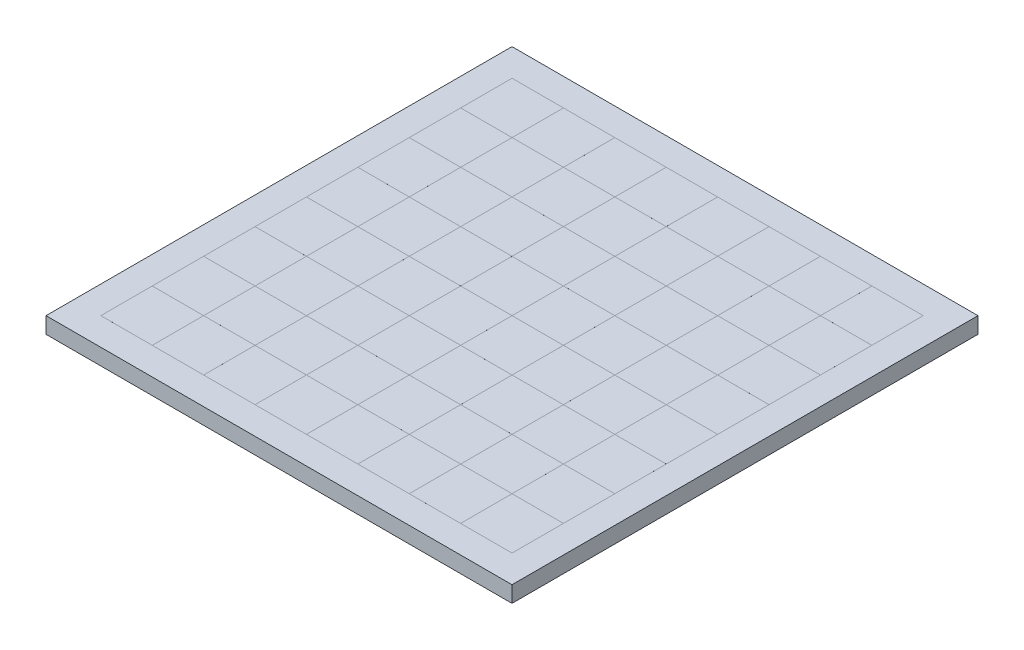
SolidWorks part; units mm, degrees
ref_plane "Front Plane" through (0, 0, 0) normal (0, 0, 1) x (1, 0, 0)
ref_plane "Top Plane" through (0, 0, 0) normal (0, 1, 0) x (1, 0, 0)
ref_plane "Right Plane" through (0, 0, 0) normal (1, 0, 0) x (0, 0, -1)
sketch "Sketch1" plane through (0, 0, 0) normal (0, 1, 0) x (1, 0, 0)
  line L1 (0, 0) -> (431.8, 0)
  line L2 (0, 0) -> (0, 431.8)
  line L3 (0, 431.8) -> (431.8, 431.8)
  line L4 (431.8, 0) -> (431.8, 431.8)
  dimension "D1" = 431.8
  dimension "D2" = 431.8
extrude "Boss-Extrude1" add sketch "Sketch1" along normal blind 5
sketch "Sketch2" plane through (0, 5, 0) normal (0, 1, 0) x (1, 0, 0)
  line L0 (0, 0) -> (431.8, 0) construction
  line L5 (25.4, 73.025) -> (73.025, 73.025)
  line L6 (25.4, 73.025) -> (25.4, 25.4)
  line L7 (25.4, 25.4) -> (73.025, 25.4)
  line L8 (73.025, 73.025) -> (73.025, 25.4)
  line L9 (0, 431.8) -> (0, 0) construction
  line L10 (25.4, 120.655) -> (25.4, 73.03)
  line L11 (25.4, 120.655) -> (73.025, 120.655)
  line L12 (73.025, 120.655) -> (73.025, 73.03)
  line L13 (25.4, 73.03) -> (73.025, 73.03)
  line L14 (25.4, 168.285) -> (25.4, 120.66)
  line L15 (25.4, 168.285) -> (73.025, 168.285)
  line L16 (73.025, 168.285) -> (73.025, 120.66)
  line L17 (25.4, 120.66) -> (73.025, 120.66)
  line L18 (25.4, 215.915) -> (25.4, 168.29)
  line L19 (25.4, 215.915) -> (73.025, 215.915)
  line L20 (73.025, 215.915) -> (73.025, 168.29)
  line L21 (25.4, 168.29) -> (73.025, 168.29)
  line L22 (25.4, 263.545) -> (25.4, 215.92)
  line L23 (25.4, 263.545) -> (73.025, 263.545)
  line L24 (73.025, 263.545) -> (73.025, 215.92)
  line L25 (25.4, 215.92) -> (73.025, 215.92)
  line L26 (25.4, 311.175) -> (25.4, 263.55)
  line L27 (25.4, 311.175) -> (73.025, 311.175)
  line L28 (73.025, 311.175) -> (73.025, 263.55)
  line L29 (25.4, 263.55) -> (73.025, 263.55)
  line L30 (25.4, 358.805) -> (25.4, 311.18)
  line L31 (25.4, 358.805) -> (73.025, 358.805)
  line L32 (73.025, 358.805) -> (73.025, 311.18)
  line L33 (25.4, 311.18) -> (73.025, 311.18)
  line L34 (25.4, 406.435) -> (25.4, 358.81)
  line L35 (25.4, 406.435) -> (73.025, 406.435)
  line L36 (73.025, 406.435) -> (73.025, 358.81)
  line L37 (25.4, 358.81) -> (73.025, 358.81)
  line L38 (73.03, 120.655) -> (73.03, 73.03)
  line L39 (73.03, 120.655) -> (120.655, 120.655)
  line L40 (120.655, 120.655) -> (120.655, 73.03)
  line L41 (73.03, 73.03) -> (120.655, 73.03)
  line L42 (73.03, 168.285) -> (73.03, 120.66)
  line L43 (73.03, 168.285) -> (120.655, 168.285)
  line L44 (120.655, 168.285) -> (120.655, 120.66)
  line L45 (73.03, 120.66) -> (120.655, 120.66)
  line L46 (73.03, 215.915) -> (73.03, 168.29)
  line L47 (73.03, 215.915) -> (120.655, 215.915)
  line L48 (120.655, 215.915) -> (120.655, 168.29)
  line L49 (73.03, 168.29) -> (120.655, 168.29)
  line L50 (73.03, 263.545) -> (73.03, 215.92)
  line L51 (73.03, 263.545) -> (120.655, 263.545)
  line L52 (120.655, 263.545) -> (120.655, 215.92)
  line L53 (73.03, 215.92) -> (120.655, 215.92)
  line L54 (73.03, 311.175) -> (73.03, 263.55)
  line L55 (73.03, 311.175) -> (120.655, 311.175)
  line L56 (120.655, 311.175) -> (120.655, 263.55)
  line L57 (73.03, 263.55) -> (120.655, 263.55)
  line L58 (73.03, 358.805) -> (73.03, 311.18)
  line L59 (73.03, 358.805) -> (120.655, 358.805)
  line L60 (120.655, 358.805) -> (120.655, 311.18)
  line L61 (73.03, 311.18) -> (120.655, 311.18)
  line L62 (73.03, 406.435) -> (73.03, 358.81)
  line L63 (73.03, 406.435) -> (120.655, 406.435)
  line L64 (120.655, 406.435) -> (120.655, 358.81)
  line L65 (73.03, 358.81) -> (120.655, 358.81)
  line L66 (120.66, 120.655) -> (120.66, 73.03)
  line L67 (120.66, 120.655) -> (168.285, 120.655)
  line L68 (168.285, 120.655) -> (168.285, 73.03)
  line L69 (120.66, 73.03) -> (168.285, 73.03)
  line L70 (120.66, 168.285) -> (120.66, 120.66)
  line L71 (120.66, 168.285) -> (168.285, 168.285)
  line L72 (168.285, 168.285) -> (168.285, 120.66)
  line L73 (120.66, 120.66) -> (168.285, 120.66)
  line L74 (120.66, 215.915) -> (120.66, 168.29)
  line L75 (120.66, 215.915) -> (168.285, 215.915)
  line L76 (168.285, 215.915) -> (168.285, 168.29)
  line L77 (120.66, 168.29) -> (168.285, 168.29)
  line L78 (120.66, 263.545) -> (120.66, 215.92)
  line L79 (120.66, 263.545) -> (168.285, 263.545)
  line L80 (168.285, 263.545) -> (168.285, 215.92)
  line L81 (120.66, 215.92) -> (168.285, 215.92)
  line L82 (120.66, 311.175) -> (120.66, 263.55)
  line L83 (120.66, 311.175) -> (168.285, 311.175)
  line L84 (168.285, 311.175) -> (168.285, 263.55)
  line L85 (120.66, 263.55) -> (168.285, 263.55)
  line L86 (120.66, 358.805) -> (120.66, 311.18)
  line L87 (120.66, 358.805) -> (168.285, 358.805)
  line L88 (168.285, 358.805) -> (168.285, 311.18)
  line L89 (120.66, 311.18) -> (168.285, 311.18)
  line L90 (120.66, 406.435) -> (120.66, 358.81)
  line L91 (120.66, 406.435) -> (168.285, 406.435)
  line L92 (168.285, 406.435) -> (168.285, 358.81)
  line L93 (120.66, 358.81) -> (168.285, 358.81)
  line L94 (168.29, 120.655) -> (168.29, 73.03)
  line L95 (168.29, 120.655) -> (215.915, 120.655)
  line L96 (215.915, 120.655) -> (215.915, 73.03)
  line L97 (168.29, 73.03) -> (215.915, 73.03)
  line L98 (168.29, 168.285) -> (168.29, 120.66)
  line L99 (168.29, 168.285) -> (215.915, 168.285)
  line L100 (215.915, 168.285) -> (215.915, 120.66)
  line L101 (168.29, 120.66) -> (215.915, 120.66)
  line L102 (168.29, 215.915) -> (168.29, 168.29)
  line L103 (168.29, 215.915) -> (215.915, 215.915)
  line L104 (215.915, 215.915) -> (215.915, 168.29)
  line L105 (168.29, 168.29) -> (215.915, 168.29)
  line L106 (168.29, 263.545) -> (168.29, 215.92)
  line L107 (168.29, 263.545) -> (215.915, 263.545)
  line L108 (215.915, 263.545) -> (215.915, 215.92)
  line L109 (168.29, 215.92) -> (215.915, 215.92)
  line L110 (168.29, 311.175) -> (168.29, 263.55)
  line L111 (168.29, 311.175) -> (215.915, 311.175)
  line L112 (215.915, 311.175) -> (215.915, 263.55)
  line L113 (168.29, 263.55) -> (215.915, 263.55)
  line L114 (168.29, 358.805) -> (168.29, 311.18)
  line L115 (168.29, 358.805) -> (215.915, 358.805)
  line L116 (215.915, 358.805) -> (215.915, 311.18)
  line L117 (168.29, 311.18) -> (215.915, 311.18)
  line L118 (168.29, 406.435) -> (168.29, 358.81)
  line L119 (168.29, 406.435) -> (215.915, 406.435)
  line L120 (215.915, 406.435) -> (215.915, 358.81)
  line L121 (168.29, 358.81) -> (215.915, 358.81)
  line L122 (215.92, 120.655) -> (215.92, 73.03)
  line L123 (215.92, 120.655) -> (263.545, 120.655)
  line L124 (263.545, 120.655) -> (263.545, 73.03)
  line L125 (215.92, 73.03) -> (263.545, 73.03)
  line L126 (215.92, 168.285) -> (215.92, 120.66)
  line L127 (215.92, 168.285) -> (263.545, 168.285)
  line L128 (263.545, 168.285) -> (263.545, 120.66)
  line L129 (215.92, 120.66) -> (263.545, 120.66)
  line L130 (215.92, 215.915) -> (215.92, 168.29)
  line L131 (215.92, 215.915) -> (263.545, 215.915)
  line L132 (263.545, 215.915) -> (263.545, 168.29)
  line L133 (215.92, 168.29) -> (263.545, 168.29)
  line L134 (215.92, 263.545) -> (215.92, 215.92)
  line L135 (215.92, 263.545) -> (263.545, 263.545)
  line L136 (263.545, 263.545) -> (263.545, 215.92)
  line L137 (215.92, 215.92) -> (263.545, 215.92)
  line L138 (215.92, 311.175) -> (215.92, 263.55)
  line L139 (215.92, 311.175) -> (263.545, 311.175)
  line L140 (263.545, 311.175) -> (263.545, 263.55)
  line L141 (215.92, 263.55) -> (263.545, 263.55)
  line L142 (215.92, 358.805) -> (215.92, 311.18)
  line L143 (215.92, 358.805) -> (263.545, 358.805)
  line L144 (263.545, 358.805) -> (263.545, 311.18)
  line L145 (215.92, 311.18) -> (263.545, 311.18)
  line L146 (215.92, 406.435) -> (215.92, 358.81)
  line L147 (215.92, 406.435) -> (263.545, 406.435)
  line L148 (263.545, 406.435) -> (263.545, 358.81)
  line L149 (215.92, 358.81) -> (263.545, 358.81)
  line L150 (263.55, 120.655) -> (263.55, 73.03)
  line L151 (263.55, 120.655) -> (311.175, 120.655)
  line L152 (311.175, 120.655) -> (311.175, 73.03)
  line L153 (263.55, 73.03) -> (311.175, 73.03)
  line L154 (263.55, 168.285) -> (263.55, 120.66)
  line L155 (263.55, 168.285) -> (311.175, 168.285)
  line L156 (311.175, 168.285) -> (311.175, 120.66)
  line L157 (263.55, 120.66) -> (311.175, 120.66)
  line L158 (263.55, 215.915) -> (263.55, 168.29)
  line L159 (263.55, 215.915) -> (311.175, 215.915)
  line L160 (311.175, 215.915) -> (311.175, 168.29)
  line L161 (263.55, 168.29) -> (311.175, 168.29)
  line L162 (263.55, 263.545) -> (263.55, 215.92)
  line L163 (263.55, 263.545) -> (311.175, 263.545)
  line L164 (311.175, 263.545) -> (311.175, 215.92)
  line L165 (263.55, 215.92) -> (311.175, 215.92)
  line L166 (263.55, 311.175) -> (263.55, 263.55)
  line L167 (263.55, 311.175) -> (311.175, 311.175)
  line L168 (311.175, 311.175) -> (311.175, 263.55)
  line L169 (263.55, 263.55) -> (311.175, 263.55)
  line L170 (263.55, 358.805) -> (263.55, 311.18)
  line L171 (263.55, 358.805) -> (311.175, 358.805)
  line L172 (311.175, 358.805) -> (311.175, 311.18)
  line L173 (263.55, 311.18) -> (311.175, 311.18)
  line L174 (263.55, 406.435) -> (263.55, 358.81)
  line L175 (263.55, 406.435) -> (311.175, 406.435)
  line L176 (311.175, 406.435) -> (311.175, 358.81)
  line L177 (263.55, 358.81) -> (311.175, 358.81)
  line L178 (311.18, 120.655) -> (311.18, 73.03)
  line L179 (311.18, 120.655) -> (358.805, 120.655)
  line L180 (358.805, 120.655) -> (358.805, 73.03)
  line L181 (311.18, 73.03) -> (358.805, 73.03)
  line L182 (311.18, 168.285) -> (311.18, 120.66)
  line L183 (311.18, 168.285) -> (358.805, 168.285)
  line L184 (358.805, 168.285) -> (358.805, 120.66)
  line L185 (311.18, 120.66) -> (358.805, 120.66)
  line L186 (311.18, 215.915) -> (311.18, 168.29)
  line L187 (311.18, 215.915) -> (358.805, 215.915)
  line L188 (358.805, 215.915) -> (358.805, 168.29)
  line L189 (311.18, 168.29) -> (358.805, 168.29)
  line L190 (311.18, 263.545) -> (311.18, 215.92)
  line L191 (311.18, 263.545) -> (358.805, 263.545)
  line L192 (358.805, 263.545) -> (358.805, 215.92)
  line L193 (311.18, 215.92) -> (358.805, 215.92)
  line L194 (311.18, 311.175) -> (311.18, 263.55)
  line L195 (311.18, 311.175) -> (358.805, 311.175)
  line L196 (358.805, 311.175) -> (358.805, 263.55)
  line L197 (311.18, 263.55) -> (358.805, 263.55)
  line L198 (311.18, 358.805) -> (311.18, 311.18)
  line L199 (311.18, 358.805) -> (358.805, 358.805)
  line L200 (358.805, 358.805) -> (358.805, 311.18)
  line L201 (311.18, 311.18) -> (358.805, 311.18)
  line L202 (311.18, 406.435) -> (311.18, 358.81)
  line L203 (311.18, 406.435) -> (358.805, 406.435)
  line L204 (358.805, 406.435) -> (358.805, 358.81)
  line L205 (311.18, 358.81) -> (358.805, 358.81)
  line L206 (358.81, 120.655) -> (358.81, 73.03)
  line L207 (358.81, 120.655) -> (406.435, 120.655)
  line L208 (406.435, 120.655) -> (406.435, 73.03)
  line L209 (358.81, 73.03) -> (406.435, 73.03)
  line L210 (358.81, 168.285) -> (358.81, 120.66)
  line L211 (358.81, 168.285) -> (406.435, 168.285)
  line L212 (406.435, 168.285) -> (406.435, 120.66)
  line L213 (358.81, 120.66) -> (406.435, 120.66)
  line L214 (358.81, 215.915) -> (358.81, 168.29)
  line L215 (358.81, 215.915) -> (406.435, 215.915)
  line L216 (406.435, 215.915) -> (406.435, 168.29)
  line L217 (358.81, 168.29) -> (406.435, 168.29)
  line L218 (358.81, 263.545) -> (358.81, 215.92)
  line L219 (358.81, 263.545) -> (406.435, 263.545)
  line L220 (406.435, 263.545) -> (406.435, 215.92)
  line L221 (358.81, 215.92) -> (406.435, 215.92)
  line L222 (358.81, 311.175) -> (358.81, 263.55)
  line L223 (358.81, 311.175) -> (406.435, 311.175)
  line L224 (406.435, 311.175) -> (406.435, 263.55)
  line L225 (358.81, 263.55) -> (406.435, 263.55)
  line L226 (358.81, 358.805) -> (358.81, 311.18)
  line L227 (358.81, 358.805) -> (406.435, 358.805)
  line L228 (406.435, 358.805) -> (406.435, 311.18)
  line L229 (358.81, 311.18) -> (406.435, 311.18)
  line L230 (358.81, 406.435) -> (358.81, 358.81)
  line L231 (358.81, 406.435) -> (406.435, 406.435)
  line L232 (406.435, 406.435) -> (406.435, 358.81)
  line L233 (358.81, 358.81) -> (406.435, 358.81)
  line L234 (73.03, 73.025) -> (73.03, 25.4)
  line L235 (73.03, 73.025) -> (120.655, 73.025)
  line L236 (120.655, 73.025) -> (120.655, 25.4)
  line L237 (73.03, 25.4) -> (120.655, 25.4)
  line L238 (120.66, 73.025) -> (120.66, 25.4)
  line L239 (120.66, 73.025) -> (168.285, 73.025)
  line L240 (168.285, 73.025) -> (168.285, 25.4)
  line L241 (120.66, 25.4) -> (168.285, 25.4)
  line L242 (168.29, 73.025) -> (168.29, 25.4)
  line L243 (168.29, 73.025) -> (215.915, 73.025)
  line L244 (215.915, 73.025) -> (215.915, 25.4)
  line L245 (168.29, 25.4) -> (215.915, 25.4)
  line L246 (215.92, 73.025) -> (215.92, 25.4)
  line L247 (215.92, 73.025) -> (263.545, 73.025)
  line L248 (263.545, 73.025) -> (263.545, 25.4)
  line L249 (215.92, 25.4) -> (263.545, 25.4)
  line L250 (263.55, 73.025) -> (263.55, 25.4)
  line L251 (263.55, 73.025) -> (311.175, 73.025)
  line L252 (311.175, 73.025) -> (311.175, 25.4)
  line L253 (263.55, 25.4) -> (311.175, 25.4)
  line L254 (311.18, 73.025) -> (311.18, 25.4)
  line L255 (311.18, 73.025) -> (358.805, 73.025)
  line L256 (358.805, 73.025) -> (358.805, 25.4)
  line L257 (311.18, 25.4) -> (358.805, 25.4)
  line L258 (358.81, 73.025) -> (358.81, 25.4)
  line L259 (358.81, 73.025) -> (406.435, 73.025)
  line L260 (406.435, 73.025) -> (406.435, 25.4)
  line L261 (358.81, 25.4) -> (406.435, 25.4)
  dimension "D1" = 47.625
  dimension "D2" = 47.625
  dimension "D3" = 25.4
  dimension "D4" = 25.4
  dimension "D5" = 8
  dimension "D6" = 8
extrude "Boss-Extrude2" add sketch "Sketch2" along normal blind 0.001
sketch "Sketch3" plane through (0, 0, 0) normal (0, -1, 0) x (1, 0, 0)
  line L4 (0, 0) -> (0, -431.8)
  line L5 (0, -431.8) -> (431.8, -431.8)
  line L6 (431.8, -431.8) -> (431.8, 0)
  line L7 (431.8, 0) -> (0, 0)
  line L8 (0, 0) -> (0, -431.8)
  line L9 (0, -431.8) -> (431.8, -431.8)
  line L10 (431.8, -431.8) -> (431.8, 0)
  line L11 (431.8, 0) -> (0, 0)
  dimension "D1" = 0
extrude "Boss-Extrude3" add sketch "Sketch3" along normal blind 10
